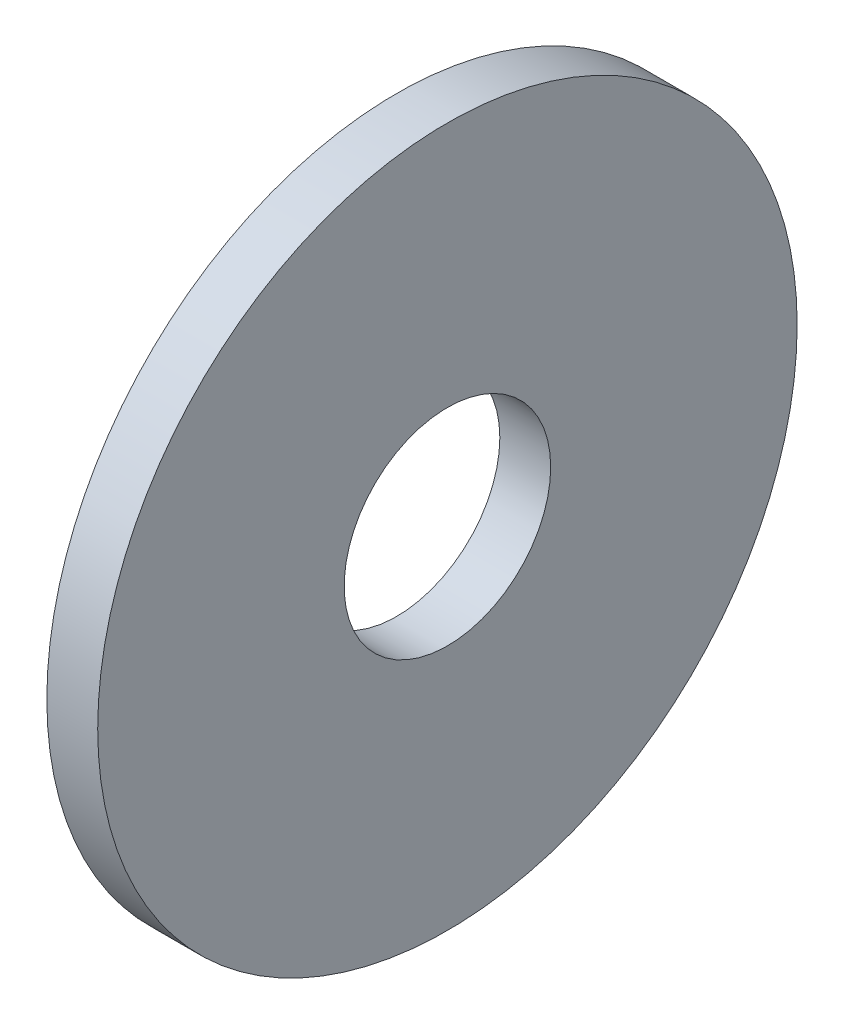
SolidWorks part; units mm, degrees
ref_plane "Front Plane" through (0, 0, 0) normal (0, 0, 1) x (1, 0, 0)
ref_plane "Top Plane" through (0, 0, 0) normal (0, 1, 0) x (1, 0, 0)
ref_plane "Right Plane" through (0, 0, 0) normal (1, 0, 0) x (0, 0, -1)
sketch "Sketch1" plane through (0, 0, 0) normal (1, 0, 0) x (0, 0, -1)
  circle A0 centre (0, 0) radius 8.7312
  circle A1 centre (0, 0) radius 2.5781
  dimension "OD" = 17.4625
  dimension "ID" = 5.1562
extrude "Boss-Extrude1" add sketch "Sketch1" along normal blind 1.27
